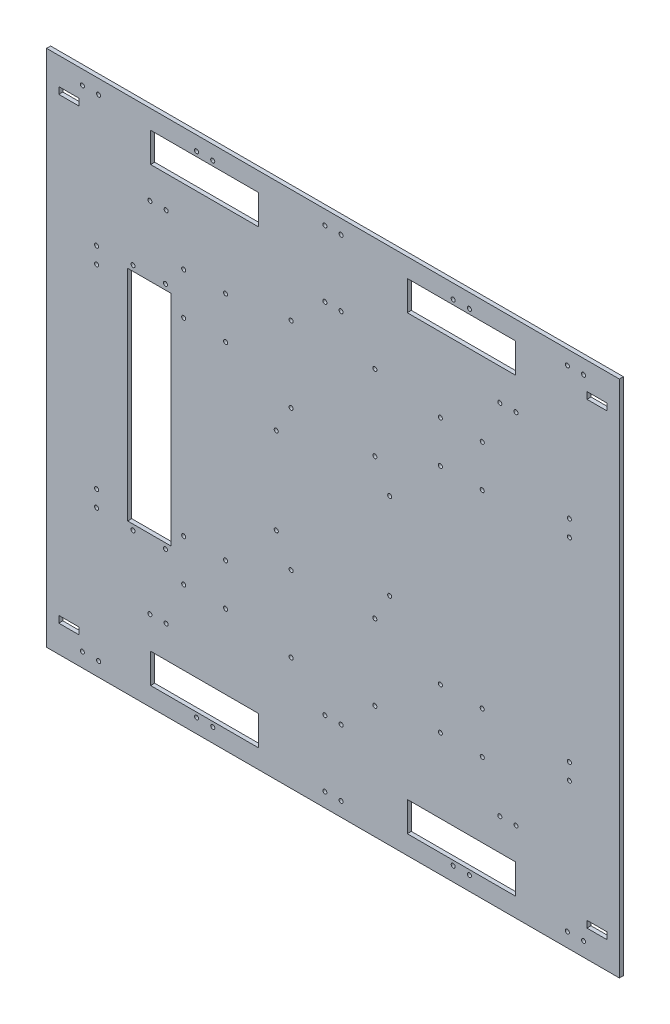
SolidWorks part; units mm, degrees
ref_plane "前视基准面" through (0, 0, 0) normal (0, 0, 1) x (1, 0, 0)
ref_plane "上视基准面" through (0, 0, 0) normal (0, 1, 0) x (1, 0, 0)
ref_plane "右视基准面" through (0, 0, 0) normal (1, 0, 0) x (0, 0, -1)
sketch "草图1" plane through (0, 0, 0) normal (0, 0, 1) x (1, 0, 0)
  line L0 (212, 384) -> (212, 0) construction
  line L1 (0, 0) -> (424, 0)
  line L2 (0, 0) -> (0, 384)
  line L3 (0, 384) -> (424, 384)
  line L4 (424, 0) -> (424, 384)
  line L5 (0, 192) -> (424, 192) construction
  line L6 (267, 370) -> (267, 348)
  line L7 (77, 370) -> (157, 370)
  line L8 (77, 370) -> (77, 348)
  line L9 (77, 348) -> (157, 348)
  line L10 (157, 370) -> (157, 348)
  line L11 (347, 370) -> (267, 370)
  line L12 (347, 370) -> (347, 348)
  line L13 (347, 348) -> (267, 348)
  line L14 (347, 14) -> (347, 36)
  line L15 (347, 14) -> (267, 14)
  line L16 (267, 14) -> (267, 36)
  line L17 (347, 36) -> (267, 36)
  line L18 (77, 14) -> (157, 14)
  line L19 (77, 36) -> (157, 36)
  line L20 (77, 14) -> (77, 36)
  line L21 (157, 14) -> (157, 36)
  dimension "D1" = 424
  dimension "D2" = 384
  dimension "D3" = 22
  dimension "D4" = 80
  dimension "D5" = 55
  dimension "D6" = 14
extrude "凸台-拉伸1" add sketch "草图1" along normal blind 3
sketch "草图2" plane through (0, 0, 3) normal (0, 0, 1) x (1, 0, 0)
  line L1 (60, 273) -> (92, 273)
  line L2 (60, 273) -> (60, 111)
  line L3 (60, 111) -> (92, 111)
  line L4 (92, 273) -> (92, 111)
  line L5 (117, 348) -> (117, 36) construction
  line L6 (77, 348) -> (157, 348) construction
  line L7 (157, 36) -> (77, 36) construction
  line L8 (0, 192) -> (424, 192) construction
  line L9 (0, 384) -> (0, 0) construction
  line L10 (424, 0) -> (424, 384) construction
  circle A0 centre (64, 277) radius 1.5
  circle A1 centre (88, 277) radius 1.5
  circle A2 centre (88, 107) radius 1.5
  circle A3 centre (64, 107) radius 1.5
  dimension "D8" = 3
  dimension "D1" = 25
  dimension "D2" = 32
  dimension "D3" = 162
  dimension "D4" = 81
  dimension "D5" = 85
  dimension "D6" = 24
  dimension "D7" = 4
extrude "切除-拉伸1" cut sketch "草图2" against normal through all
sketch "草图3" plane through (0, 0, 3) normal (0, 0, 1) x (1, 0, 0)
  line L0 (0, 192) -> (424, 192) construction
  line L1 (0, 384) -> (0, 0) construction
  line L2 (424, 0) -> (424, 384) construction
  line L3 (212, 384) -> (212, 0) construction
  line L4 (424, 384) -> (0, 384) construction
  line L5 (0, 0) -> (424, 0) construction
  line L6 (117, 370) -> (117, 348) construction
  line L7 (157, 370) -> (77, 370) construction
  line L8 (77, 348) -> (157, 348) construction
  circle A0 centre (101.5, 293) radius 1.5
  circle A1 centre (132.5, 293) radius 1.5
  circle A2 centre (101.5, 262) radius 1.5
  circle A3 centre (132.5, 262) radius 1.5
  circle A4 centre (322.5, 262) radius 1.5
  circle A5 centre (291.5, 262) radius 1.5
  circle A6 centre (291.5, 293) radius 1.5
  circle A7 centre (322.5, 293) radius 1.5
  circle A8 centre (291.5, 122) radius 1.5
  circle A9 centre (322.5, 122) radius 1.5
  circle A10 centre (322.5, 91) radius 1.5
  circle A11 centre (291.5, 91) radius 1.5
  circle A12 centre (101.5, 122) radius 1.5
  circle A13 centre (132.5, 122) radius 1.5
  circle A14 centre (132.5, 91) radius 1.5
  circle A15 centre (101.5, 91) radius 1.5
  dimension "D5" = 3
  dimension "D1" = 31
  dimension "D2" = 31
  dimension "D3" = 91
  dimension "D4" = 15.5
extrude "切除-拉伸2" cut sketch "草图3" against normal through all
sketch "草图4" plane through (0, 0, 3) normal (0, 0, 1) x (1, 0, 0)
  line L0 (0, 192) -> (424, 192) construction
  line L1 (0, 384) -> (0, 0) construction
  line L2 (424, 0) -> (424, 384) construction
  line L3 (212, 384) -> (212, 0) construction
  line L4 (424, 384) -> (0, 384) construction
  line L5 (0, 0) -> (424, 0) construction
  line L6 (307, 36) -> (307, 14) construction
  line L7 (347, 36) -> (267, 36) construction
  line L8 (267, 14) -> (347, 14) construction
  circle A0 centre (218, 10.5) radius 1.5
  circle A1 centre (301, 10.5) radius 1.5
  circle A2 centre (313, 10.5) radius 1.5
  circle A3 centre (385.5, 10.5) radius 1.5
  circle A4 centre (397.5, 10.5) radius 1.5
  circle A5 centre (218, 59.5) radius 1.5
  circle A6 centre (335.5, 59.5) radius 1.5
  circle A7 centre (347.5, 59.5) radius 1.5
  circle A8 centre (387, 108) radius 1.5
  circle A9 centre (387, 120) radius 1.5
  circle A10 centre (387, 276) radius 1.5
  circle A11 centre (387, 264) radius 1.5
  circle A12 centre (301, 373.5) radius 1.5
  circle A13 centre (313, 373.5) radius 1.5
  circle A14 centre (397.5, 373.5) radius 1.5
  circle A15 centre (385.5, 373.5) radius 1.5
  circle A16 centre (347.5, 324.5) radius 1.5
  circle A17 centre (335.5, 324.5) radius 1.5
  circle A18 centre (218, 373.5) radius 1.5
  circle A19 centre (206, 59.5) radius 1.5
  circle A20 centre (206, 10.5) radius 1.5
  circle A21 centre (111, 10.5) radius 1.5
  circle A22 centre (123, 10.5) radius 1.5
  circle A23 centre (26.5, 10.5) radius 1.5
  circle A24 centre (38.5, 10.5) radius 1.5
  circle A25 centre (76.5, 59.5) radius 1.5
  circle A26 centre (88.5, 59.5) radius 1.5
  circle A27 centre (37, 108) radius 1.5
  circle A28 centre (37, 120) radius 1.5
  circle A29 centre (37, 264) radius 1.5
  circle A30 centre (37, 276) radius 1.5
  circle A31 centre (26.5, 373.5) radius 1.5
  circle A32 centre (38.5, 373.5) radius 1.5
  circle A33 centre (76.5, 324.5) radius 1.5
  circle A34 centre (88.5, 324.5) radius 1.5
  circle A35 centre (111, 373.5) radius 1.5
  circle A36 centre (123, 373.5) radius 1.5
  circle A37 centre (206, 373.5) radius 1.5
  circle A38 centre (206, 324.5) radius 1.5
  circle A39 centre (218, 324.5) radius 1.5
  dimension "D1" = 3
  dimension "D2" = 6
  dimension "D3" = 10.5
  dimension "D4" = 12
  dimension "D5" = 6
  dimension "D6" = 12
  dimension "D7" = 173.5
  dimension "D8" = 59.5
  dimension "D9" = 123.5
  dimension "D10" = 12
  dimension "D11" = 175
  dimension "D12" = 120
  dimension "D13" = 12
extrude "切除-拉伸3" cut sketch "草图4" against normal through all
sketch "草图5" plane through (0, 0, 3) normal (0, 0, 1) x (1, 0, 0)
  line L0 (424, 384) -> (0, 384) construction
  line L1 (9, 364) -> (24, 364)
  line L2 (9, 364) -> (9, 359)
  line L3 (9, 359) -> (24, 359)
  line L4 (24, 364) -> (24, 359)
  line L5 (0, 384) -> (0, 0) construction
  line L6 (212, 384) -> (212, 0) construction
  line L7 (0, 0) -> (424, 0) construction
  line L8 (0, 192) -> (424, 192) construction
  line L9 (424, 0) -> (424, 384) construction
  line L10 (415, 364) -> (400, 364)
  line L11 (400, 364) -> (400, 359)
  line L12 (415, 359) -> (400, 359)
  line L13 (415, 364) -> (415, 359)
  line L14 (415, 20) -> (415, 25)
  line L15 (415, 25) -> (400, 25)
  line L16 (400, 20) -> (400, 25)
  line L17 (415, 20) -> (400, 20)
  line L18 (24, 20) -> (24, 25)
  line L19 (9, 25) -> (24, 25)
  line L20 (9, 20) -> (9, 25)
  line L21 (9, 20) -> (24, 20)
  dimension "D1" = 5
  dimension "D2" = 15
  dimension "D3" = 20
  dimension "D4" = 9
extrude "切除-拉伸4" cut sketch "草图5" against normal through all
sketch "草图6" plane through (0, 0, 3) normal (0, 0, 1) x (1, 0, 0)
  line L0 (0, 192) -> (424, 192) construction
  line L1 (0, 384) -> (0, 0) construction
  line L2 (424, 0) -> (424, 384) construction
  line L3 (212, 384) -> (212, 0) construction
  line L4 (424, 384) -> (0, 384) construction
  line L5 (0, 0) -> (424, 0) construction
  circle A0 centre (170, 224) radius 1.5
  circle A1 centre (170, 160) radius 1.5
  circle A2 centre (254, 160) radius 1.5
  circle A3 centre (254, 224) radius 1.5
  circle A4 centre (181, 300) radius 1.5
  circle A5 centre (243, 300) radius 1.5
  circle A6 centre (243, 244) radius 1.5
  circle A7 centre (181, 244) radius 1.5
  circle A8 centre (181, 140) radius 1.5
  circle A9 centre (243, 140) radius 1.5
  circle A10 centre (243, 84) radius 1.5
  circle A11 centre (181, 84) radius 1.5
  dimension "D1" = 3
  dimension "D2" = 84
  dimension "D3" = 64
  dimension "D4" = 42
  dimension "D5" = 32
  dimension "D6" = 62
  dimension "D7" = 56
  dimension "D8" = 31
  dimension "D9" = 20
extrude "切除-拉伸5" cut sketch "草图6" against normal through all
